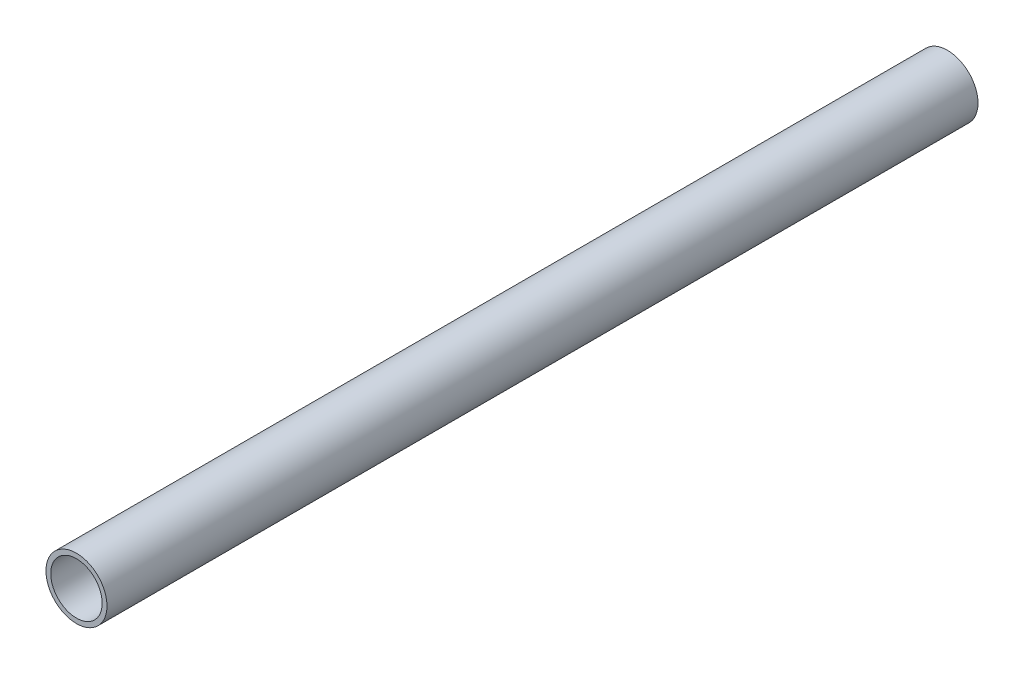
SolidWorks part; units mm, degrees
ref_plane "Front Plane" through (0, 0, 0) normal (0, 0, 1) x (1, 0, 0)
ref_plane "Top Plane" through (0, 0, 0) normal (0, 1, 0) x (1, 0, 0)
ref_plane "Right Plane" through (0, 0, 0) normal (1, 0, 0) x (0, 0, -1)
sketch "Sketch1" plane through (0, 0, 0) normal (0, 0, 1) x (1, 0, 0)
  line L0 (-7.9375, 0) -> (7.9375, 0) construction
  line L1 (0, -7.9375) -> (0, 7.9375) construction
  circle A0 centre (0, 0) radius 7.9375
  circle A1 centre (0, 0) radius 6.6929
  point P4 (0, 0)
  point P9 (0, 0)
  point P10 (6.6929, 0)
  dimension "ID" = 13.3858
  dimension "OD" = 15.875
  dimension "Wall Thickness" = 1.2446
sketch "Sketch2" plane through (0, 0, 0) normal (1, 0, 0) x (0, 0, -1)
  line L0 (113.2962, 7.9375) -> (-113.2962, 7.9375) construction
  line L1 (0, 7.9375) -> (0, -7.9375) construction
  point P3 (-95.0399, 7.9375)
  point P4 (0, 7.9375)
  point P5 (95.0399, 7.9375)
  dimension "Length" = 226.5924
  dimension "D1" = 18.2563
  dimension "D2" = 18.2562
sketch "Sketch3" plane through (0, 0, 0) normal (0, 0, 1) x (1, 0, 0)
  line L0 (0, -7.9375) -> (0, 7.9375) construction
  circle A0 centre (0, 0) radius 7.9375
  circle A1 centre (0, 0) radius 6.6929
  circle A2 centre (0, 0) radius 6.6929 construction
extrude "Boss-Extrude1" add sketch "Sketch3" along normal mid plane 226.5924
equation "\"D1@Boss-Extrude1\" = \"Length@Sketch2\""
equation "\"D1@Sketch2\"=\"OD@Sketch1\"*1.15"
equation "\"D2@Sketch2\"=\"D1@Sketch2\""
